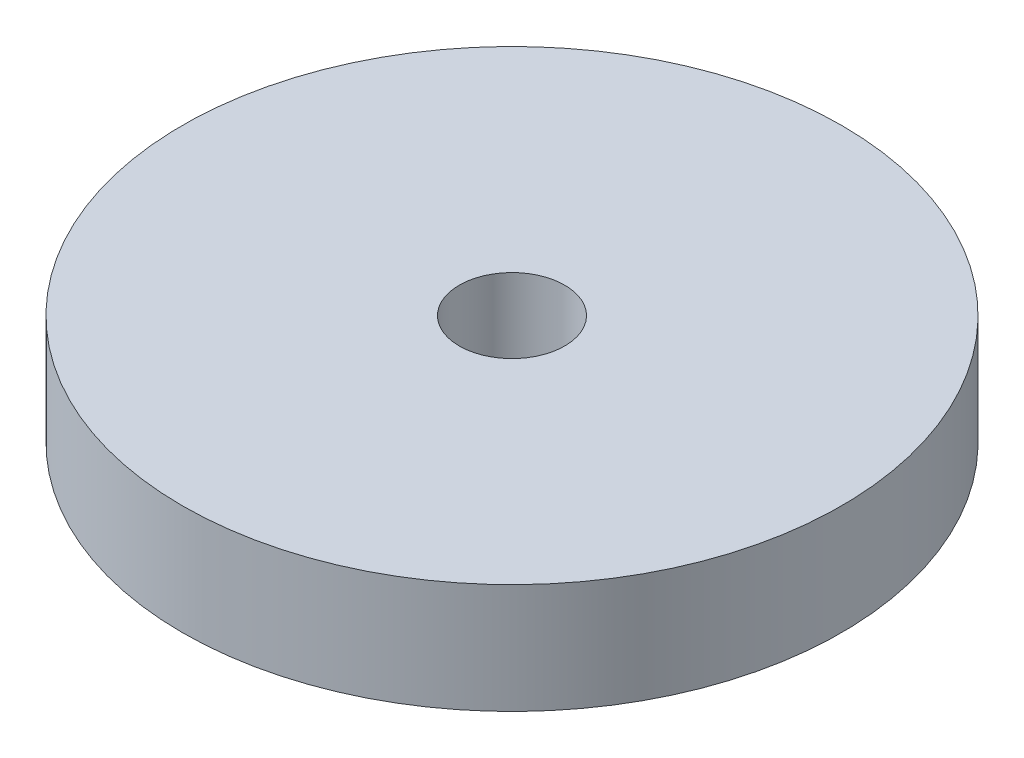
SolidWorks part; units mm, degrees
ref_plane "Front Plane" through (0, 0, 0) normal (0, 0, 1) x (1, 0, 0)
ref_plane "Top Plane" through (0, 0, 0) normal (0, 1, 0) x (1, 0, 0)
ref_plane "Right Plane" through (0, 0, 0) normal (1, 0, 0) x (0, 0, -1)
sketch "Sketch1" plane through (0, 0, 0) normal (0, 1, 0) x (1, 0, 0)
  circle A0 centre (0, 0) radius 2.4
  circle A1 centre (0, 0) radius 15
  dimension "D1" = 30
  dimension "D2" = 4.8
extrude "Boss-Extrude1" add sketch "Sketch1" along normal blind 5
